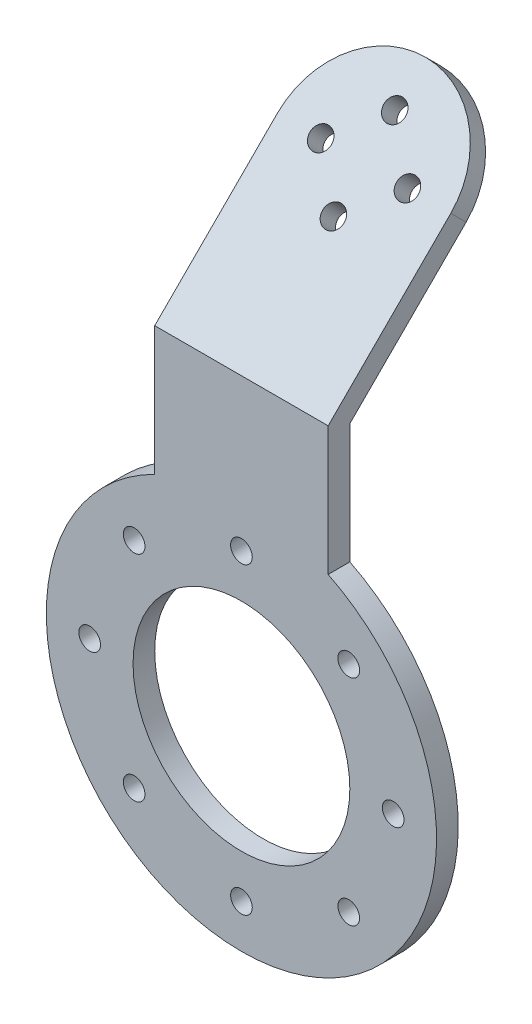
SolidWorks part; units mm, degrees
other "DetailItem14"
material "Plain Carbon Steel"
ref_plane "Front Plane" through (0, 0, 0) normal (0, 0, 1) x (1, 0, 0)
ref_plane "Top Plane" through (0, 0, 0) normal (0, 1, 0) x (1, 0, 0)
ref_plane "Right Plane" through (0, 0, 0) normal (1, 0, 0) x (0, 0, -1)
sketch "Sketch1" plane through (0, 0, 0) normal (0, 0, 1) x (1, 0, 0)
  line L0 (0, 64.2293) -> (0, 0) construction
  line L2 (-12.7, 25.5977) -> (-12.7, 44.45)
  line L3 (-12.7, 44.45) -> (12.7, 44.45)
  line L4 (12.7, 25.5977) -> (12.7, 44.45)
  circle A0 centre (0, 0) radius 15.875
  arc A1 (-12.7, 25.5977) -> (12.7, 25.5977) centre (0, 0) ccw
  dimension "D1" = 31.75
  dimension "D2" = 57.15
  dimension "D3" = 44.45
  dimension "D4" = 25.4
extrude "Extrude1" add sketch "Sketch1" along normal blind 3.175
ref_plane "Plane1" through (0, 23.8125, 23.8125) normal (0, 0.7071, 0.7071) x (-1, 0, 0)
sketch "Sketch2" plane through (0, 23.8125, 23.8125) normal (0, 0.7071, 0.7071) x (-1, 0, 0)
  line L0 (12.7, -29.1858) -> (12.7, -54.5858)
  line L1 (-12.7, -54.5858) -> (-12.7, -29.1858)
  line L2 (-12.7, -29.1858) -> (12.7, -29.1858) construction
  line L3 (12.7, -29.1858) -> (-12.7, -29.1858)
  arc A0 (12.7, -54.5858) -> (-12.7, -54.5858) centre (0, -54.5858) cw
  dimension "D2" = 25.4
extrude "Extrude2" add sketch "Sketch2" against normal blind 3.175
sketch "Sketch3" plane through (0, 0, 3.175) normal (0, 0, 1) x (1, 0, 0)
  line L0 (0, 0) -> (0, 59.0296) construction
  circle A0 centre (0, 0) radius 22.225 construction
  circle A1 centre (0, 22.225) radius 1.5875
  dimension "D1" = 3.175
extrude "Extrude3" cut sketch "Sketch3" against normal through all
pattern_circular "CirPattern1" count 8 over 360 about axis through (0, 0, 0) along (0, 0, 1) of "Extrude3"
sketch "Sketch4" plane through (0, 23.8125, 23.8125) normal (0, 0.7071, 0.7071) x (1, 0, 0)
  line L0 (0, 54.5858) -> (0, 81.8829) construction
  circle A0 centre (0, 54.5858) radius 6.35 construction
  circle A1 centre (0, 60.9358) radius 1.5875
  dimension "D1" = 12.7
  dimension "D2" = 3.175
extrude "Extrude4" cut sketch "Sketch4" against normal through all
pattern_circular "CirPattern2" count 4 over 360 about axis through (0, 38.598, -38.598) along (0, 0.7071, 0.7071) of "Extrude4"
